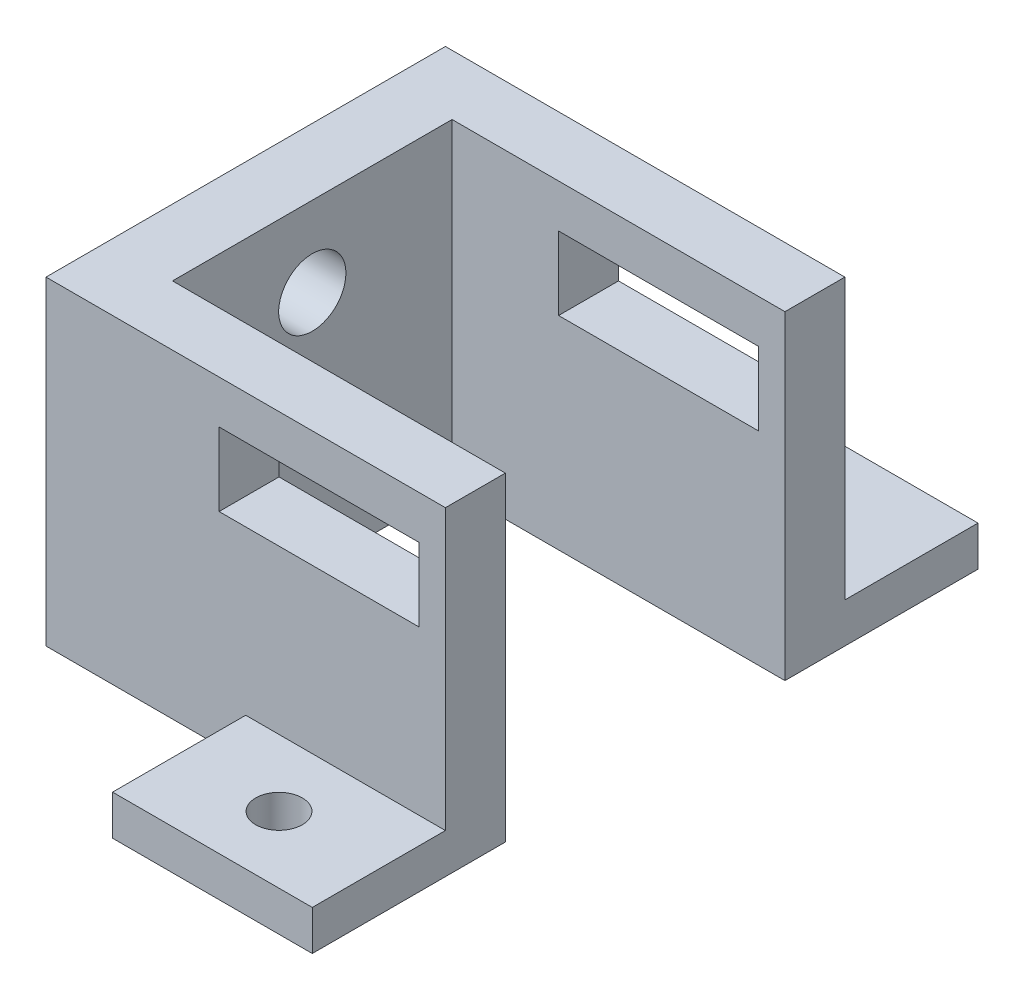
SolidWorks part; units mm, degrees
ref_plane "Front Plane" through (0, 0, 0) normal (0, 0, 1) x (1, 0, 0)
ref_plane "Top Plane" through (0, 0, 0) normal (0, 1, 0) x (1, 0, 0)
ref_plane "Right Plane" through (0, 0, 0) normal (1, 0, 0) x (0, 0, -1)
sketch "Sketch1" plane through (0, 0, 0) normal (0, 0, 1) x (1, 0, 0)
  line L1 (-15, -12) -> (15, -12)
  line L2 (-15, -12) -> (-15, 12)
  line L3 (-15, 12) -> (15, 12)
  line L4 (15, -12) -> (15, 12)
  line L5 (-15, -12) -> (15, 12) construction
  line L6 (-15, 12) -> (15, -12) construction
  line L7 (13, 3.25) -> (-2, 3.25)
  line L8 (13, 3.25) -> (13, 8.75)
  line L9 (13, 8.75) -> (-2, 8.75)
  line L10 (-2, 3.25) -> (-2, 8.75)
  line L11 (13, 3.25) -> (-2, 8.75) construction
  line L12 (13, 8.75) -> (-2, 3.25) construction
  point P0 (0, 0)
  point P6 (5.5, 6)
  point P7 (5.5, 6)
  dimension "D1" = 5.5
  dimension "D3" = 24
  dimension "D4" = 15
  dimension "D5" = 2
  dimension "D6" = 18
  dimension "D2" = 30
extrude "Boss-Extrude1" add sketch "Sketch1" along normal blind 30
sketch "Sketch2" plane through (15, 0, 0) normal (1, 0, 0) x (0, 0, -1)
  line L0 (0, -12) -> (0, 12) construction
  line L1 (-30, -12) -> (0, -12) construction
  line L2 (-30, -12) -> (-30, 12) construction
  line L3 (-30, 12) -> (0, 12) construction
  line L4 (0, -12) -> (0, 12) construction
  line L5 (-25.5, -12) -> (-4.5, -12)
  line L6 (-30, -12) -> (-30, 12) construction
  line L7 (-25.5, 12) -> (-4.5, 12)
  line L8 (-30, 12) -> (0, -12) construction
  line L9 (-30, 12) -> (-25.5, 12) construction
  line L10 (-25.5, -12) -> (-4.5, -12)
  line L11 (-25.5, -12) -> (-25.5, 12)
  line L12 (-25.5, 12) -> (-4.5, 12)
  line L13 (-4.5, -12) -> (-4.5, 12)
  line L14 (-25.5, -12) -> (-4.5, 12) construction
  line L15 (-25.5, 12) -> (-4.5, -12) construction
  line L16 (-30, -12) -> (-25.5, -12) construction
  line L17 (-4.5, -12) -> (0, -12) construction
  line L18 (-4.5, 12) -> (0, 12) construction
  point P3 (-15, 0)
  point P5 (-15, 0)
  line M5 (0, 12) -> (-30, 12)
  line M7 (-30, -12) -> (0, -12)
  dimension "D1" = 21
extrude "Cut-Extrude1" cut sketch "Sketch2" against normal blind 25 contours L13 L11 M7 M5
sketch "Sketch3" plane through (-10, 0, 0) normal (1, 0, 0) x (0, 0, -1)
  line L0 (-25.5, 12) -> (-4.5, -12) construction
  line L1 (-25.5, -12) -> (-4.5, 12) construction
  line L2 (-15, 0) -> (-15, 12) construction
  line L3 (-4.5, 12) -> (-15, 12) construction
  line L4 (-25.5, -12) -> (-4.5, -12)
  line L5 (-4.5, -12) -> (-4.5, 12)
  line L6 (-4.5, 12) -> (-25.5, 12)
  line L7 (-25.5, 12) -> (-25.5, -12)
  line L8 (-25.5, -12) -> (-4.5, -12) construction
  line L9 (-4.5, -12) -> (-4.5, 12) construction
  line L10 (-15, 12) -> (-25.5, 12) construction
  line L11 (-25.5, 12) -> (-25.5, -12) construction
  circle A0 centre (-15, 6) radius 2.525
  point P6 (-15, 6)
  dimension "D2" = 5.05
  dimension "D3" = 18
  dimension "D1" = 0
extrude "Cut-Extrude2" cut sketch "Sketch3" against normal through all
sketch "Эскиз1" plane through (0, 0, 30) normal (0, 0, 1) x (1, 0, 0)
  line L1 (15, -12) -> (0, -12)
  line L2 (15, -12) -> (15, -9)
  line L3 (15, -9) -> (0, -9)
  line L4 (0, -12) -> (0, -9)
  dimension "D1" = 3
  dimension "D2" = 15
extrude "Бобышка-Вытянуть1" add sketch "Эскиз1" along normal blind 10
sketch "Эскиз2" plane through (0, 0, 0) normal (0, 0, -1) x (-1, 0, 0)
  line L1 (-15, -12) -> (0, -12)
  line L2 (-15, -12) -> (-15, -9)
  line L3 (-15, -9) -> (0, -9)
  line L4 (0, -12) -> (0, -9)
  dimension "D1" = 15
  dimension "D2" = 3
extrude "Бобышка-Вытянуть2" add sketch "Эскиз2" along normal blind 10
sketch "Эскиз3" plane through (0, -9, 0) normal (0, 1, 0) x (1, 0, 0)
  line L0 (0, -35) -> (15, -35) construction
  line L1 (0, -40) -> (0, -30) construction
  line L2 (15, -40) -> (15, -30) construction
  line L3 (7.5, -40) -> (7.5, -30) construction
  line L4 (15, -40) -> (0, -40) construction
  line L5 (15, -30) -> (-15, -30) construction
  circle A1 centre (7.5, -35) radius 1.75
  dimension "D1" = 3.5
extrude "Вырез-Вытянуть1" cut sketch "Эскиз3" against normal through all
sketch "Эскиз4" plane through (0, -9, 0) normal (0, 1, 0) x (1, 0, 0)
  line L0 (0, 5) -> (15, 5) construction
  line L1 (0, 10) -> (0, 0) construction
  line L2 (15, 10) -> (15, 0) construction
  line L3 (7.5, 0) -> (7.5, 10) construction
  line L4 (13, 0) -> (-2, 0) construction
  line L5 (0, 10) -> (15, 10) construction
  circle A0 centre (7.5, 5) radius 1.75
  dimension "D1" = 3.5
extrude "Вырез-Вытянуть2" cut sketch "Эскиз4" against normal through all
equation "\"lengtMain\"= 50mm"
equation "\"D1@Cut-Extrude1\"=\"lengtMain\"-5mm"
equation "\"holeHeigth\"= 18mm"
equation "\"D6@Sketch1\"=\"holeHeigth\""
equation "\"D3@Sketch3\"=\"holeHeigth\""
